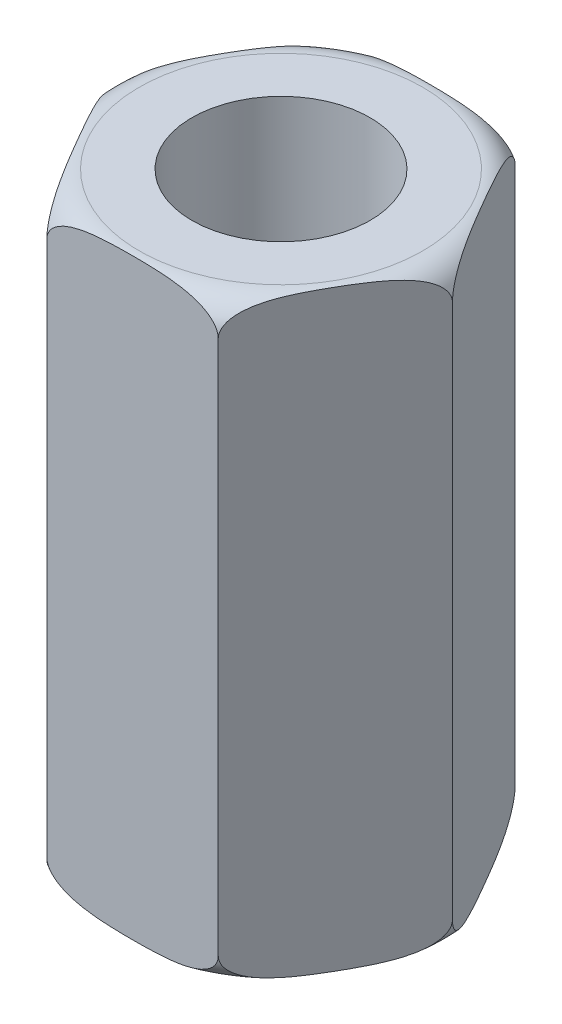
SolidWorks part; units mm, degrees
ref_plane "Plan de face" through (0, 0, 0) normal (0, 0, 1) x (1, 0, 0)
ref_plane "Plan de dessus" through (0, 0, 0) normal (0, 1, 0) x (1, 0, 0)
ref_plane "Plan de droite" through (0, 0, 0) normal (1, 0, 0) x (0, 0, -1)
sketch "Esquisse1" plane through (0, 0, 0) normal (0, 1, 0) x (1, 0, 0)
  line L1 (2.8868, 0) -> (1.4434, 2.5)
  line L2 (1.4434, 2.5) -> (-1.4434, 2.5)
  line L3 (-1.4434, 2.5) -> (-2.8868, 0)
  line L4 (-2.8868, 0) -> (-1.4434, -2.5)
  line L5 (-1.4434, -2.5) -> (1.4434, -2.5)
  line L6 (1.4434, -2.5) -> (2.8868, 0)
  circle A0 centre (0, 0) radius 2.5 construction
  circle A1 centre (0, 0) radius 1.5
  dimension "D1" = 3
  dimension "D2" = 1
extrude "Boss.-Extru.1" add sketch "Esquisse1" along normal blind 10
sketch "Esquisse3" plane through (0, 0, 0) normal (0, 0, 1) x (1, 0, 0)
  line L2 (2.3868, 10) -> (2.8868, 10)
  line L3 (2.8868, 10) -> (2.8868, 9.5)
  line L5 (2.8868, 0.5) -> (2.8868, 0)
  line L6 (2.8868, 0) -> (2.3868, 0)
  arc A0 (2.8868, 9.5) -> (2.3868, 10) centre (2.3868, 9.5) ccw
  arc A1 (2.8868, 0.5) -> (2.3868, 0) centre (2.3868, 0.5) cw
  point P2 (0, 0)
  dimension "D1" = 0.5
  dimension "D2" = 0.5
ref_axis "Axe1" through (0, -0.5, 0) along (0, 1, 0)
revolve "Enlèvement de matière-Révolution1" cut sketch "Esquisse3" angle 360 about axis through (0, -0.5, 0) along (0, 1, 0)
